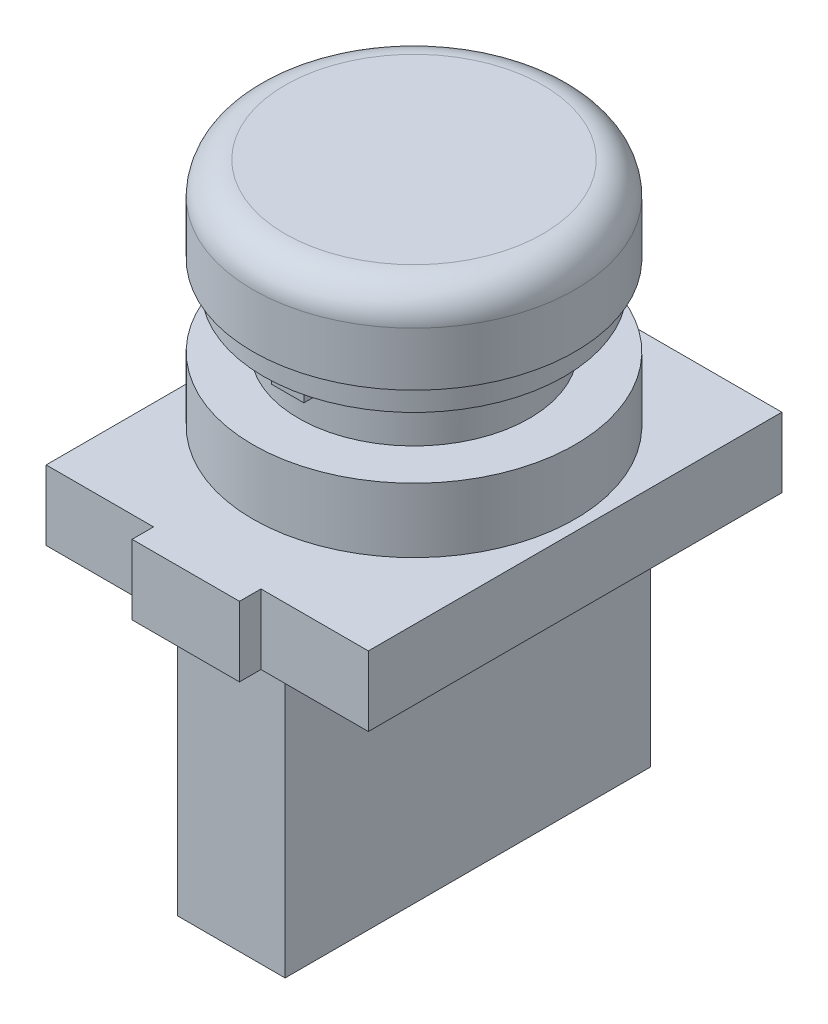
SolidWorks part; units mm, degrees
material "ABS"
ref_plane "Ebene vorne" through (0, 0, 0) normal (0, 0, 1) x (1, 0, 0)
ref_plane "Ebene oben" through (0, 0, 0) normal (0, 1, 0) x (1, 0, 0)
ref_plane "Ebene rechts" through (0, 0, 0) normal (1, 0, 0) x (0, 0, -1)
sketch "Skizze1" plane through (0, 0, 0) normal (0, 1, 0) x (1, 0, 0)
  circle A0 centre (0, 0) radius 14
  dimension "D1" = 28
extrude "Aufsatz-Linear austragen1" add sketch "Skizze1" along normal blind 2.5
sketch "Skizze2" plane through (0, 2.5, 0) normal (0, 1, 0) x (1, 0, 0)
  circle A0 centre (0, 0) radius 15
  dimension "D1" = 30
extrude "Aufsatz-Linear austragen2" add sketch "Skizze2" along normal blind 8
fillet "Verrundung1" radius 3 1 edges at (0, 10.5, 15)
sketch "Skizze3" plane through (0, 0, 0) normal (0, -1, 0) x (1, 0, 0)
  line L0 (0, 0) -> (0, 10.75) construction
  line L2 (-1.5, 11.75) -> (1.5, 11.75)
  line L3 (-1.5, 11.75) -> (-1.5, 9.75)
  line L4 (-1.5, 9.75) -> (1.5, 9.75)
  line L5 (1.5, 11.75) -> (1.5, 9.75)
  line L6 (-1.5, 11.75) -> (1.5, 9.75) construction
  line L7 (-1.5, 9.75) -> (1.5, 11.75) construction
  circle A0 centre (0, 0) radius 10.75
  dimension "D1" = 21.5
  dimension "D2" = 3
  dimension "D3" = 2
extrude "Aufsatz-Linear austragen3" add sketch "Skizze3" along normal blind 2.5 contours L3 A0 L5 L4
sketch "Skizze4" plane through (0, -2.5, 0) normal (0, -1, 0) x (1, 0, 0)
  circle A0 centre (0, 0) radius 10.75
  dimension "D1" = 21.5
extrude "Aufsatz-Linear austragen4" add sketch "Skizze4" along normal blind 2.5
sketch "Skizze5" plane through (0, -5, 0) normal (0, -1, 0) x (1, 0, 0)
  circle A0 centre (0, 0) radius 15
  dimension "D1" = 30
extrude "Aufsatz-Linear austragen5" add sketch "Skizze5" along normal blind 6
sketch "Skizze6" plane through (0, -11, 0) normal (0, -1, 0) x (1, 0, 0)
  circle A0 centre (0, 0) radius 10.75
  dimension "D1" = 21.5
extrude "Aufsatz-Linear austragen6" add sketch "Skizze6" along normal blind 1
sketch "Skizze7" plane through (0, -12, 0) normal (0, -1, 0) x (1, 0, 0)
  line L1 (-15, 19.25) -> (15, 19.25)
  line L2 (-15, 19.25) -> (-15, -19.25)
  line L3 (-15, -19.25) -> (15, -19.25)
  line L4 (15, 19.25) -> (15, -19.25)
  line L5 (-15, 19.25) -> (15, -19.25) construction
  line L6 (-15, -19.25) -> (15, 19.25) construction
  line L7 (-5, 21.25) -> (5, 21.25)
  line L8 (-5, 21.25) -> (-5, 17.25)
  line L9 (-5, 17.25) -> (5, 17.25)
  line L10 (5, 21.25) -> (5, 17.25)
  line L11 (-5, 21.25) -> (5, 17.25) construction
  line L12 (-5, 17.25) -> (5, 21.25) construction
  point P0 (0, 0)
  point P6 (0, 19.25)
  circle M5 centre (0, 0) radius 10.75
  dimension "D1" = 30
  dimension "D2" = 38.5
  dimension "D3" = 4
  dimension "D4" = 10
extrude "Aufsatz-Linear austragen7" add sketch "Skizze7" along normal blind 6.5 separate body contours L1 L10 L9 L8 L2 L3 L4 M5 | M5
sketch "Skizze8" plane through (0, -18.5, 0) normal (0, -1, 0) x (1, 0, 0)
  line L1 (-5, 17) -> (5, 17)
  line L2 (-5, 17) -> (-5, -17)
  line L3 (-5, -17) -> (5, -17)
  line L4 (5, 17) -> (5, -17)
  line L5 (-5, 17) -> (5, -17) construction
  line L6 (-5, -17) -> (5, 17) construction
  point P0 (0, 0)
  dimension "D1" = 10
  dimension "D2" = 34
extrude "Aufsatz-Linear austragen8" add sketch "Skizze8" along normal blind 26
